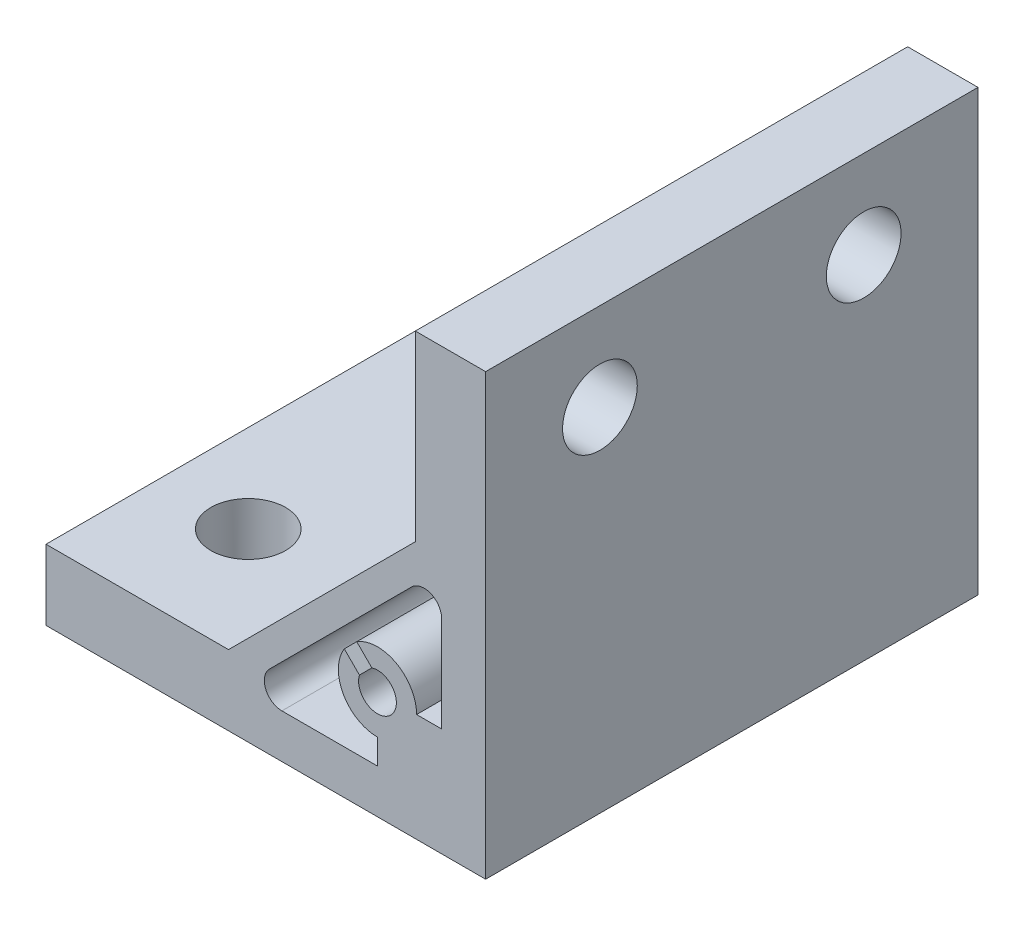
SolidWorks part; units mm, degrees
ref_plane "前视基准面" through (0, 0, 0) normal (0, 0, 1) x (1, 0, 0)
ref_plane "上视基准面" through (0, 0, 0) normal (0, 1, 0) x (1, 0, 0)
ref_plane "右视基准面" through (0, 0, 0) normal (1, 0, 0) x (0, 0, -1)
sketch "草图1" plane through (0, 0, 0) normal (0, 0, 1) x (1, 0, 0)
  line B0 (0, 0) -> (50, 0)
  line B1 (50, 0) -> (50, 50)
  line B2 (0, 8) -> (20.7574, 8)
  line B3 (42, 29.2426) -> (42, 50)
  line B4 (0, 8) -> (0, 0)
  line B5 (42, 50) -> (50, 50)
  line B6 (37.0613, 14.3529) -> (35.341, 16.0733)
  line B7 (35.6471, 12.9387) -> (33.9267, 14.659)
  line B8 (25.4142, 8.4142) -> (41.5858, 24.5858)
  line B9 (20.7574, 8) -> (42, 29.2426)
  line B10 (26.8284, 5) -> (37.7, 5)
  line B11 (45, 23.1716) -> (45, 12.3)
  line B12 (37.7, 5) -> (37.7, 7.85)
  line B13 (42.15, 12.3) -> (45, 12.3)
  arc B14 (33.9267, 14.659) -> (37.7, 7.85) centre (37.7, 12.3) ccw
  arc B15 (42.15, 12.3) -> (35.341, 16.0733) centre (37.7, 12.3) ccw
  arc B16 (35.6471, 12.9387) -> (37.0613, 14.3529) centre (37.7, 12.3) ccw
  arc B17 (25.4142, 8.4142) -> (26.8284, 5) centre (26.8284, 7) ccw
  arc B18 (45, 23.1716) -> (41.5858, 24.5858) centre (43, 23.1716) ccw
sketch_block_instance "A$C19004297-1"
sketch_block "A$C19004297"
extrude "凸台-拉伸1" add sketch "草图1" along normal mid plane 56
sketch "草图3" plane through (0, 8, 0) normal (0, 1, 0) x (1, 0, 0)
  line L0 (0, 0) -> (20.7574, 0) construction
  line L1 (0, -28) -> (0, 28) construction
  line L2 (20.7574, -28) -> (20.7574, 28) construction
  circle A0 centre (10, 15) radius 4.25
  circle A1 centre (10, -15) radius 4.25
  dimension "D1" = 10
  dimension "D2" = 15
extrude "切除-拉伸1" cut sketch "草图3" against normal blind 56
sketch "草图4" plane through (6.3787, -6.3787, 0) normal (-0.7071, 0.7071, 0) x (0, 0, 1)
  line L0 (28, 35.3553) -> (-28, 35.3553) construction
  line L1 (28, 50.3762) -> (28, 20.3345) construction
  line L2 (-28, 50.3762) -> (-28, 20.3345) construction
ref_plane "基准面2" through (25, 25, 0) normal (-0.7071, -0.7071, 0) x (0, 0, 1)
mirror "镜向1" about plane through (25, 25, 0) normal (-0.7071, -0.7071, 0) of "切除-拉伸1"
